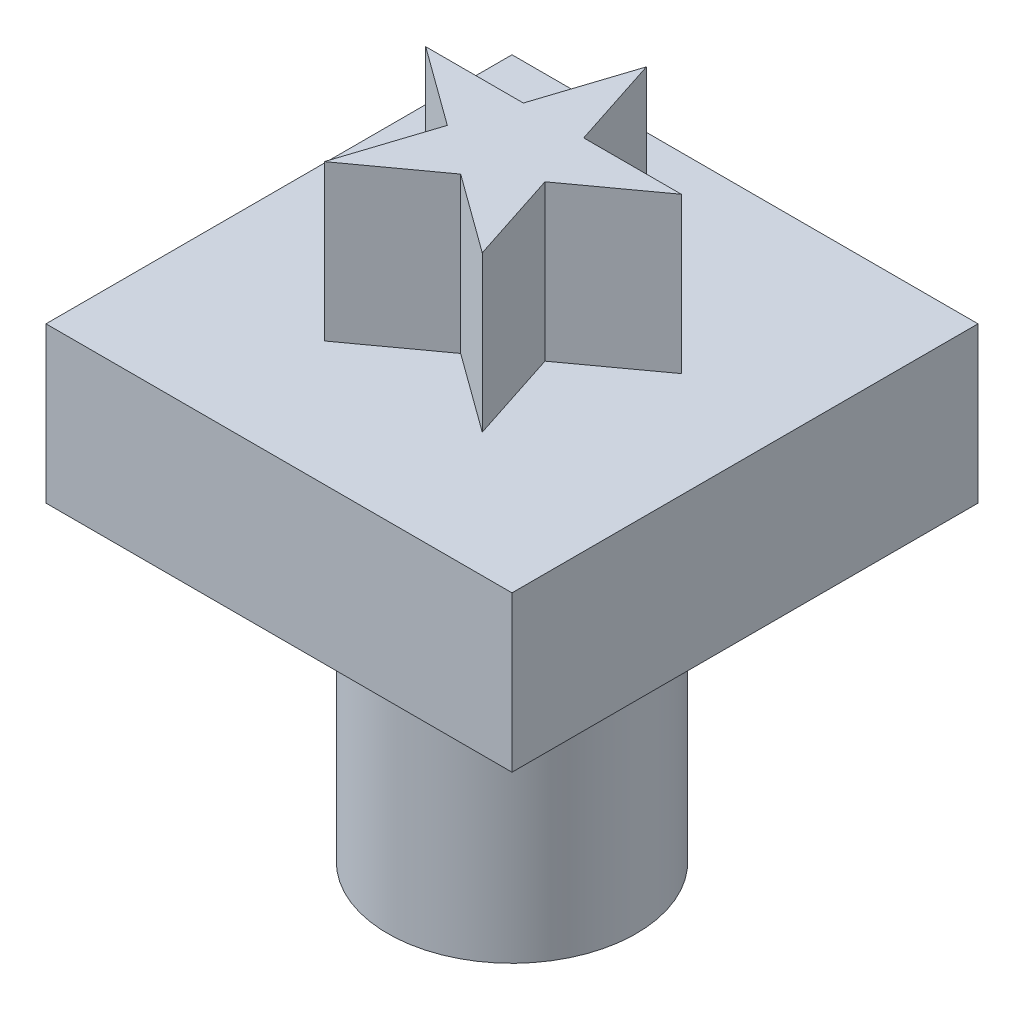
SolidWorks part; units mm, degrees
ref_plane "Front Plane" through (0, 0, 0) normal (0, 0, 1) x (1, 0, 0)
ref_plane "Top Plane" through (0, 0, 0) normal (0, 1, 0) x (1, 0, 0)
ref_plane "Right Plane" through (0, 0, 0) normal (1, 0, 0) x (0, 0, -1)
sketch "Sketch1" plane through (0, 0, 0) normal (0, 1, 0) x (1, 0, 0)
  line L1 (7.5, -7.5) -> (-7.5, -7.5)
  line L2 (7.5, -7.5) -> (7.5, 7.5)
  line L3 (7.5, 7.5) -> (-7.5, 7.5)
  line L4 (-7.5, -7.5) -> (-7.5, 7.5)
  line L5 (7.5, -7.5) -> (-7.5, 7.5) construction
  line L6 (7.5, 7.5) -> (-7.5, -7.5) construction
  point P0 (0, 0)
  dimension "D1" = 15
  dimension "D2" = 15
extrude "Boss-Extrude1" add sketch "Sketch1" along normal blind 5
sketch "Sketch5" plane through (0, 0, 0) normal (0, -1, 0) x (1, 0, 0)
  circle A0 centre (0, 0) radius 4
  dimension "D1" = 8
extrude "Boss-Extrude3" add sketch "Sketch5" along normal blind 10
sketch "Sketch6" plane through (0, 5, 0) normal (0, 1, 0) x (1, 0, 0)
  line L0 (-2.5429, -3.5) -> (-1.5716, -0.5106)
  line L6 (2.5429, -3.5) -> (1.5716, -0.5106)
  line L7 (-4.1145, 1.3369) -> (-0.9713, 1.3369)
  line L8 (4.1145, 1.3369) -> (1.5716, -0.5106)
  line L9 (2.5429, -3.5) -> (0, -1.6525)
  line L10 (-1.5716, -0.5106) -> (-4.1145, 1.3369)
  line L11 (0.9713, 1.3369) -> (4.1145, 1.3369)
  line L12 (-0.9713, 1.3369) -> (0, 4.3262)
  line L13 (0.9713, 1.3369) -> (0, 4.3262)
  line L14 (0, -1.6525) -> (-2.5429, -3.5)
  arc A1 (-2.271, -2.6632) -> (-1.8311, -2.9828) centre (0, 0) ccw construction
extrude "Boss-Extrude4" add sketch "Sketch6" along normal blind 5
equation "\"Base_side\"= 15mm"
equation "\"Base_thickness\"= 5mm"
equation "\"Connector_dia\"= 8mm"
equation "\"Connector_height\"= 10mm"
equation "\"Indenter_thickness\"= 5mm"
equation "\"Draft_angle\"= 0deg"
equation "\"D1@Boss-Extrude4\"=\"Indenter_thickness\""
equation "\"D2@Sketch1\"=\"Base_side\""
equation "\"D3@Boss-Extrude4\"=\"Draft_angle\""
equation "\"D1@Sketch1\"=\"Base_side\""
equation "\"D1@Boss-Extrude1\"=\"Base_thickness\""
equation "\"D1@Sketch5\"=\"Connector_dia\""
equation "\"D1@Boss-Extrude3\"=\"Connector_height\""
